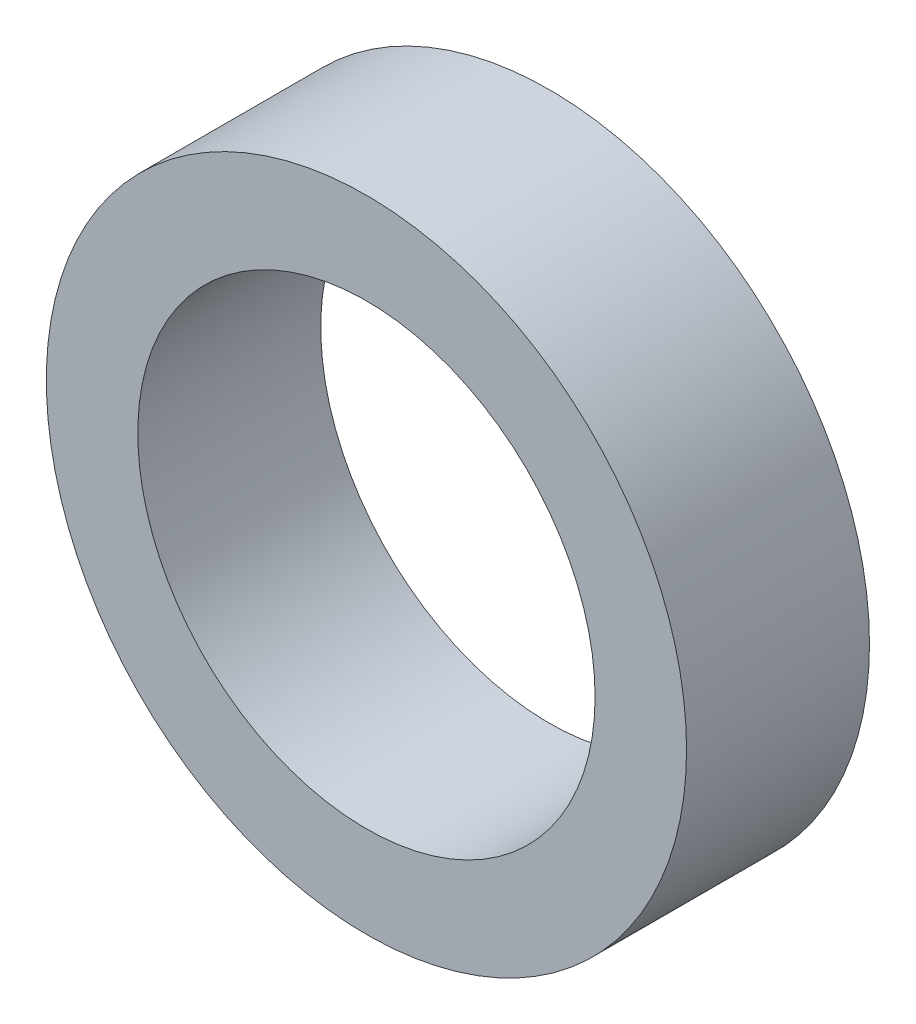
SolidWorks part; units mm, degrees
ref_plane "Front Plane" through (0, 0, 0) normal (1, 0, 0) x (0, 1, 0)
ref_plane "Top Plane" through (0, 0, 0) normal (0, 0, 1) x (0, 1, 0)
ref_plane "Right Plane" through (0, 0, 0) normal (0, 1, 0) x (-1, 0, 0)
sketch "Sketch1" plane through (0, 0, 0) normal (0, 0, 1) x (0, 1, 0)
  circle A0 centre (0, 0) radius 7.9375
  circle A1 centre (0, 0) radius 11.1125
  dimension "D1" = 15.875
  dimension "D2" = 3.175
extrude "Boss-Extrude1" add sketch "Sketch1" along normal blind 6.35
